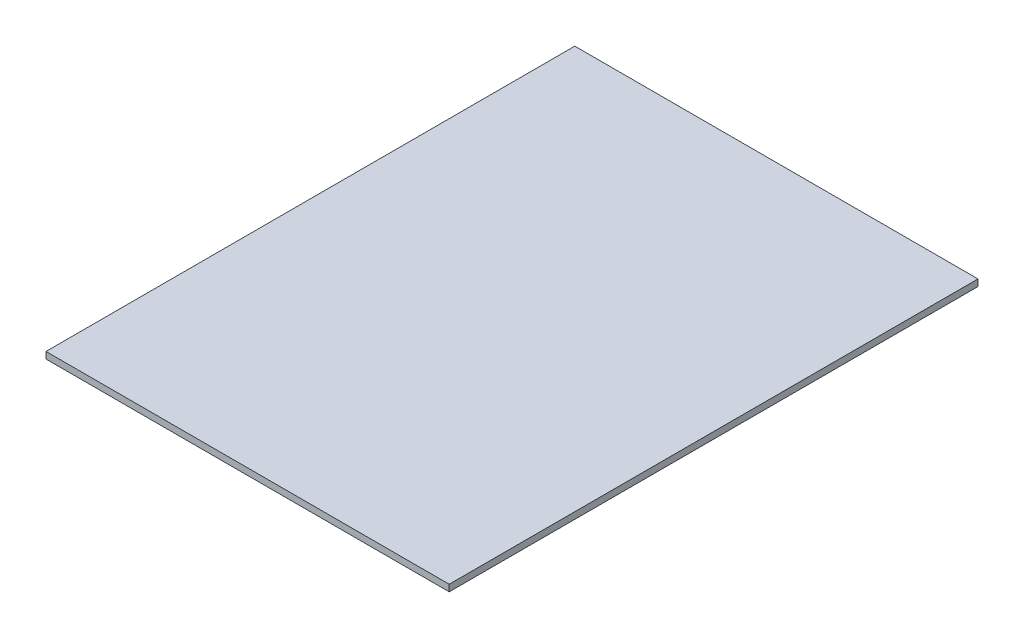
SolidWorks part; units mm, degrees
ref_plane "Front Plane" through (0, 0, 0) normal (0, 0, 1) x (1, 0, 0)
ref_plane "Top Plane" through (0, 0, 0) normal (0, 1, 0) x (1, 0, 0)
ref_plane "Right Plane" through (0, 0, 0) normal (1, 0, 0) x (0, 0, -1)
sketch "Sketch1" plane through (0, 0, 0) normal (0, 1, 0) x (1, 0, 0)
  line L1 (-193.675, 254) -> (193.675, 254)
  line L2 (-193.675, 254) -> (-193.675, -254)
  line L3 (-193.675, -254) -> (193.675, -254)
  line L4 (193.675, 254) -> (193.675, -254)
  point P4 (0, 254)
  point P5 (-193.675, 0)
  dimension "D1" = 508
  dimension "D2" = 387.35
extrude "Boss-Extrude1" add sketch "Sketch1" along normal blind 6.35
